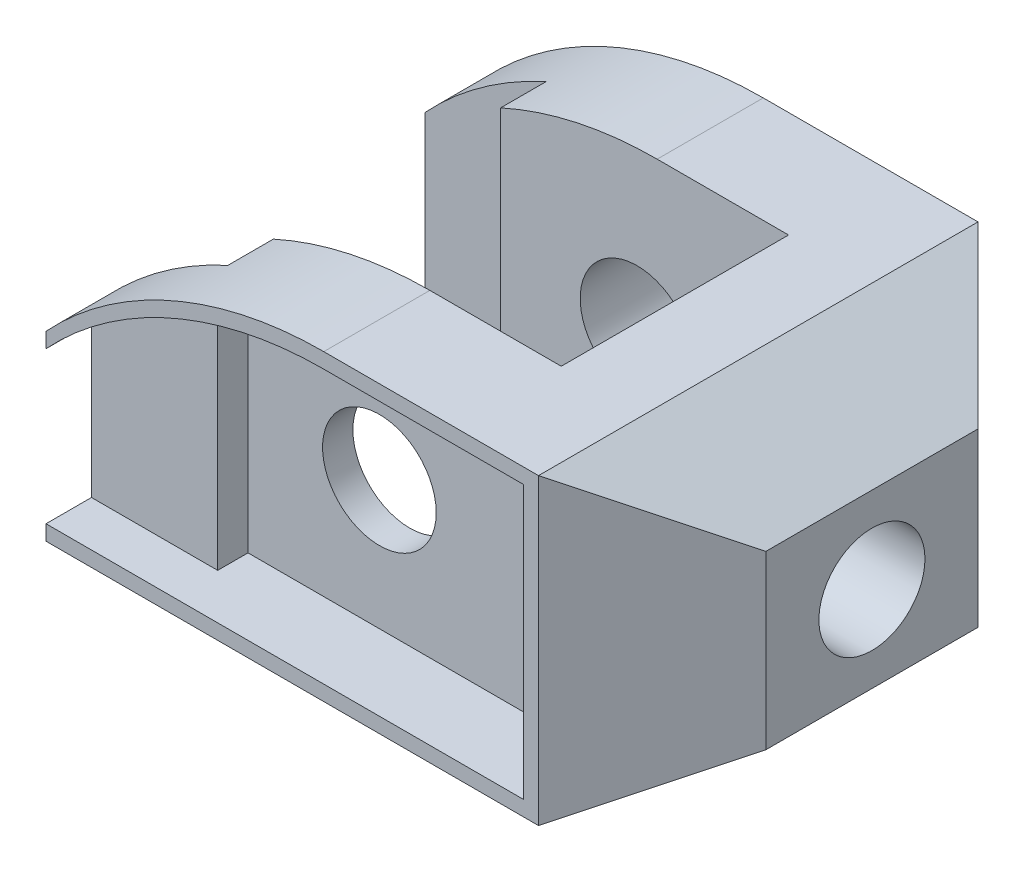
SolidWorks part; units mm, degrees
material "1060 Alloy"
ref_plane "Front Plane" through (0, 0, 0) normal (0, 0, 1) x (1, 0, 0)
ref_plane "Top Plane" through (0, 0, 0) normal (0, 1, 0) x (1, 0, 0)
ref_plane "Right Plane" through (0, 0, 0) normal (1, 0, 0) x (0, 0, -1)
sketch "Sketch1" plane through (0, 0, 0) normal (0, 1, 0) x (1, 0, 0)
  line L1 (40, -29) -> (-40, -29)
  line L2 (40, -29) -> (40, 29)
  line L3 (40, 29) -> (-40, 29)
  line L4 (-40, -29) -> (-40, 29)
  line L5 (40, -29) -> (-40, 29) construction
  line L6 (40, 29) -> (-40, -29) construction
  point P0 (0, 0)
  dimension "D1" = 58
  dimension "D2" = 80
extrude "Boss-Extrude1" add sketch "Sketch1" along normal blind 40
sketch "Sketch2" plane through (0, 0, 29) normal (0, 0, 1) x (1, 0, 0)
  line L0 (25, 40) -> (40, 40)
  line L1 (-40, 40) -> (40, 40) construction
  line L2 (40, 40) -> (40, 31.3397)
  line L3 (40, 40) -> (40, 0) construction
  line L4 (40, 31.3397) -> (25, 40)
  line L5 (-40, 19) -> (40, 19) construction
  line L7 (40, 0) -> (40, 8.6603)
  line L8 (40, 8.6603) -> (25, 0)
  line L9 (25, 0) -> (40, 0)
  line L11 (-40, 40) -> (-40, 0) construction
  line L12 (-40, 0) -> (40, 0) construction
  line L13 (-40, 0) -> (-40, 24)
  line L14 (-40, 24) -> (-40, 40)
  circle A0 centre (-6, 19) radius 7.5
  arc A3 (37.3914, 19) -> (-40, 24) centre (-3.3394, -10) ccw
  dimension "D4" = 15
  dimension "D7" = 15
  dimension "kd" = 100
  dimension "D1" = 15
  dimension "D2" = 30
  dimension "D3" = 19
  dimension "D5" = 31
  dimension "D6" = 24
  dimension "D8" = 65
  dimension "D9" = 30
  dimension "D11" = 40
extrude "Cut-Extrude1" cut sketch "Sketch2" against normal through all
sketch "Sketch3" plane through (0, 0, 0) normal (0, 1, 0) x (1, 0, 0)
  line L0 (-40, 0) -> (40, 0) construction
  line L1 (25, 29) -> (40, 29)
  line L2 (-40, 29) -> (-40, -29) construction
  line L3 (40, 29) -> (40, -29) construction
  line L4 (40, 29) -> (40, 14)
  line L5 (40, 14) -> (25, 29)
  line L6 (40, -14) -> (25, -29)
  line L7 (40, -29) -> (40, -14)
  line L8 (25, -29) -> (40, -29)
  line L9 (-40, 21) -> (-24, 21)
  line L10 (25, 29) -> (25, -29) construction
  line L11 (-24, 21) -> (-24, 15)
  line L12 (-24, 15) -> (14, 15)
  line L13 (14, 15) -> (14, -15)
  line L14 (-3.3394, 29) -> (-40, 29) construction
  line L15 (-24, -15) -> (14, -15)
  line L16 (-24, -21) -> (-24, -15)
  line L17 (-40, -21) -> (-24, -21)
  line L18 (-40, 21) -> (-40, -21)
  point P24 (14, 0)
  dimension "D1" = 45
  dimension "D2" = 8
  dimension "D3" = 6
  dimension "D4" = 16
  dimension "D5" = 11
extrude "Cut-Extrude6" cut sketch "Sketch3" along normal through all
sketch "Sketch4" plane through (40, 0, 0) normal (1, 0, 0) x (0, 0, -1)
  line L1 (14, 31.3397) -> (-14, 31.3397) construction
  line L2 (0, 31.3397) -> (0, 8.6603) construction
  line L3 (14, 8.6603) -> (-14, 8.6603) construction
  circle A0 centre (0, 20) radius 7
  dimension "D1" = 14
extrude "Cut-Extrude7" cut sketch "Sketch4" against normal through all
sketch "Sketch5" plane through (0, 0, 29) normal (0, 0, 1) x (1, 0, 0)
  line L0 (-40, 2) -> (23, 2)
  line L1 (23, 2) -> (23, 38)
  line L2 (23, 38) -> (-3.3394, 38)
  line L3 (-40, 24) -> (-40, 0) construction
  line L4 (-40, 0) -> (25, 0) construction
  line L5 (-3.3394, 40) -> (25, 40) construction
  line L6 (-40, 22) -> (-40, 2)
  line L7 (25, 40) -> (25, 0) construction
  arc A0 (-3.3394, 38) -> (-40, 22) centre (-3.3394, -12) ccw
  dimension "D4" = 100
  dimension "D1" = 2
  dimension "D2" = 2
  dimension "D3" = 2
extrude "Cut-Extrude8" cut sketch "Sketch5" against normal blind 6
sketch "Sketch6" plane through (0, 0, 23) normal (0, 0, 1) x (1, 0, 0)
  line L0 (-23.3394, 33.8258) -> (-23.3394, 2)
  line L2 (-40, 2) -> (23, 2) construction
  line L3 (-23.3394, 2) -> (23, 2)
  line L4 (23, 2) -> (23, 38) construction
  line L5 (23, 2) -> (23, 38)
  line L6 (23, 38) -> (-3.3394, 38)
  line L7 (23, 38) -> (-3.3394, 38) construction
  arc A2 (-3.3394, 38) -> (-23.3394, 33.8258) centre (-3.3394, -12) ccw
  dimension "D1" = 100
extrude "Cut-Extrude9" cut sketch "Sketch6" against normal blind 4
equation "\"a\"= 58mm"
equation "\"b\"= 40mm"
equation "\"c\"= 65mm"
